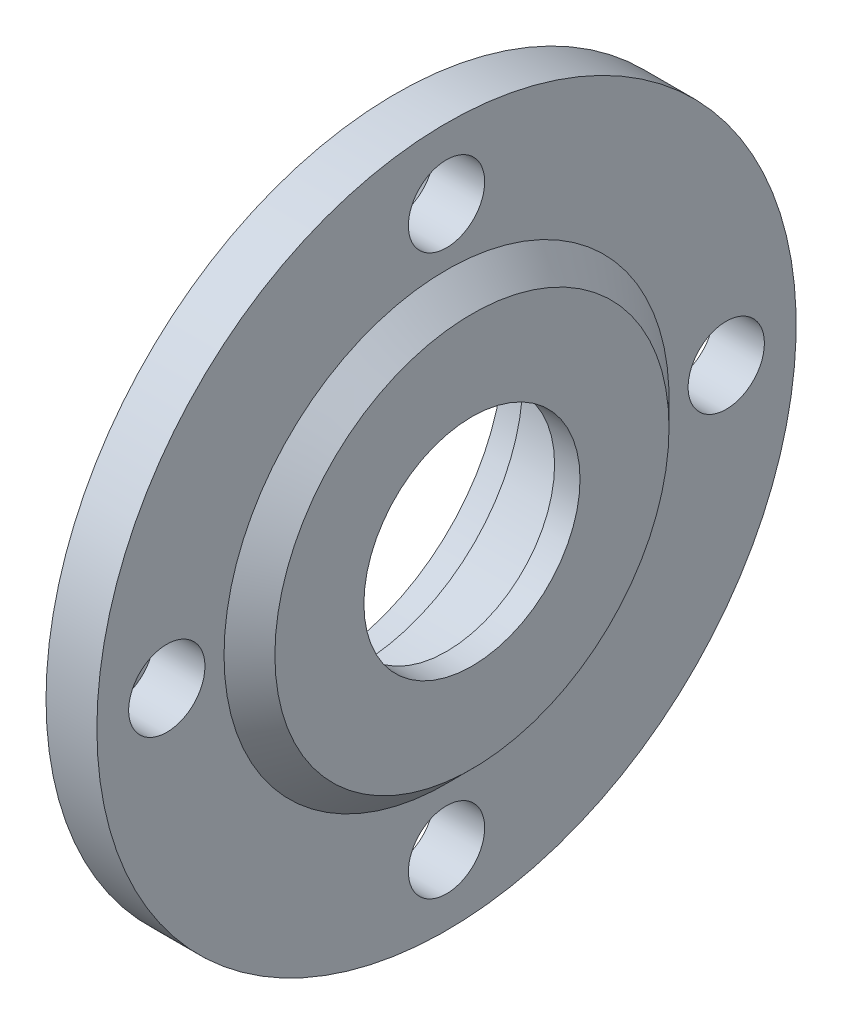
SolidWorks part; units mm, degrees
ref_plane "Front Plane" through (0, 0, 0) normal (0, 0, 1) x (1, 0, 0)
ref_plane "Top Plane" through (0, 0, 0) normal (0, 1, 0) x (1, 0, 0)
ref_plane "Right Plane" through (0, 0, 0) normal (1, 0, 0) x (0, 0, -1)
sketch "Sketch2" plane through (0, 0, 0) normal (0, 1, 0) x (1, 0, 0)
  line L0 (0, 0) -> (38.1023, 0) construction
  line L1 (18.8922, 8.5) -> (20.8922, 8.5)
  line L2 (20.8922, 8.5) -> (20.8922, 15.5)
  line L3 (20.8922, 15.5) -> (18.8922, 17.5)
  line L4 (18.8922, 17.5) -> (18.8922, 27.5)
  line L5 (18.8922, 27.5) -> (14.8922, 27.5)
  line L6 (14.8922, 27.5) -> (14.8922, 17.5)
  line L7 (14.8922, 17.5) -> (8.8922, 17.5)
  line L8 (8.8922, 17.5) -> (8.8922, 14.5)
  line L9 (8.8922, 14.5) -> (11.8922, 14.5)
  line L10 (11.8922, 14.5) -> (11.8922, 13)
  line L11 (11.8922, 13) -> (18.8922, 13)
  line L12 (18.8922, 13) -> (18.8922, 8.5)
  point P5 (0, 0)
  point P16 (0, 0)
  dimension "D1" = 17
  dimension "D2" = 3
  dimension "D3" = 29
  dimension "D4" = 26
  dimension "D5" = 55
  dimension "D6" = 35
  dimension "D7" = 4
  dimension "D8" = 12
  dimension "D9" = 7
  dimension "D10" = 2
  dimension "D11" = 6
  dimension "D12" = 45
revolve "Revolve1" add sketch "Sketch2" angle 360 about L0
sketch "Sketch3" plane through (18.8922, 0, 0) normal (1, 0, 0) x (0, 0, -1)
  circle A0 centre (0, 0) radius 22 construction
  circle A1 centre (0, 22) radius 3
  circle A2 centre (22, 0) radius 3
  circle A3 centre (0, -22) radius 3
  circle A4 centre (-22, 0) radius 3
  point P14 (0, 0)
  dimension "D1" = 4
extrude "Cut-Extrude1" cut sketch "Sketch3" against normal through all
